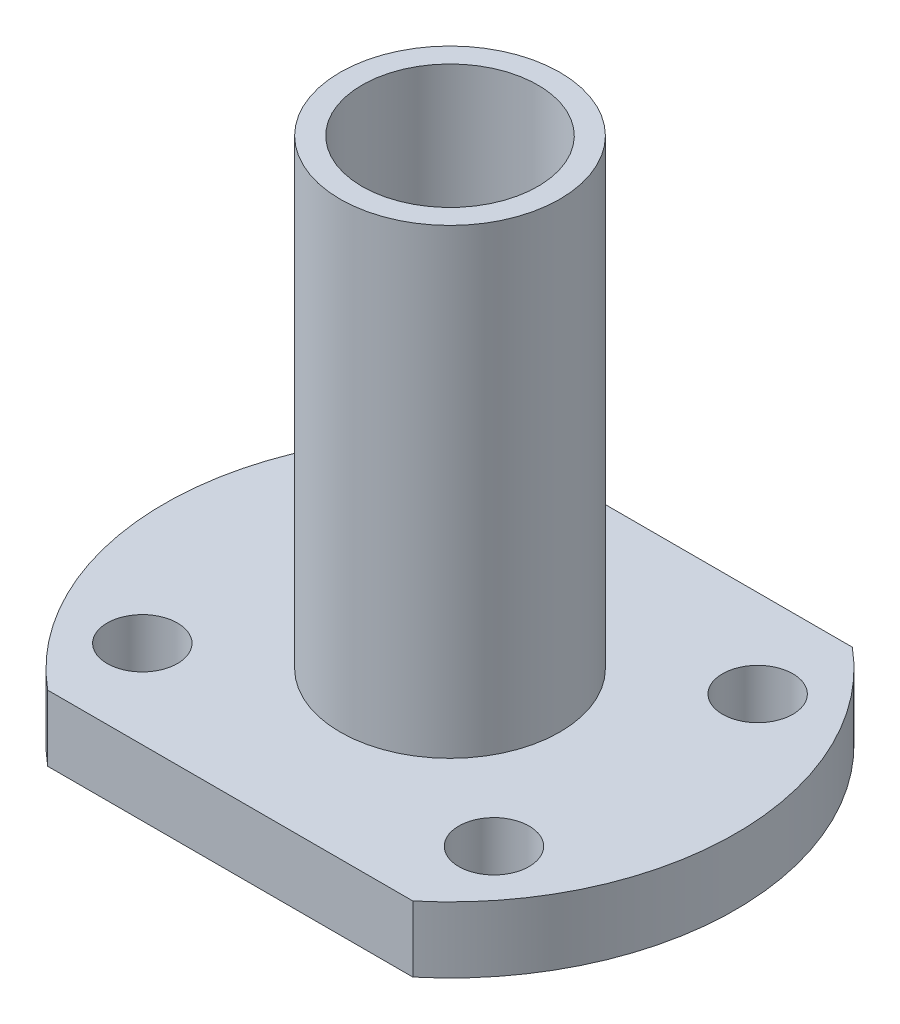
SolidWorks part; units mm, degrees
material "AISI 304"
ref_plane "Front Plane" through (0, 0, 0) normal (0, 0, 1) x (1, 0, 0)
ref_plane "Top Plane" through (0, 0, 0) normal (0, 1, 0) x (1, 0, 0)
ref_plane "Right Plane" through (0, 0, 0) normal (1, 0, 0) x (0, 0, -1)
sketch "Sketch1" plane through (0, 0, 0) normal (0, 1, 0) x (1, 0, 0)
  circle A0 centre (0, 0) radius 5
  dimension "D1" = 10
extrude "Boss-Extrude1" add sketch "Sketch1" along normal blind 24 contours A0
ref_plane "Plane1" through (0, 0, 0) normal (0, 1, 0) x (1, 0, 0)
sketch "Sketch2" plane through (0, 0, 0) normal (0, 1, 0) x (1, 0, 0)
  line L1 (-13, 10) -> (13, 10)
  line L2 (-13, 10) -> (-13, -10)
  line L3 (-13, -10) -> (13, -10)
  line L4 (13, 10) -> (13, -10)
  line L5 (-13, 10) -> (13, -10) construction
  line L6 (-13, -10) -> (13, 10) construction
  circle A0 centre (0, 0) radius 13
  dimension "D1" = 26
  dimension "D2" = 20
extrude "Boss-Extrude2" add sketch "Sketch2" along normal blind 3 contours L3 A0 L1
sketch "Sketch3" plane through (0, 24, 0) normal (0, 1, 0) x (1, 0, 0)
  circle A0 centre (0, 0) radius 4
  dimension "D1" = 8
extrude "Cut-Extrude1" cut sketch "Sketch3" against normal through all
sketch "Sketch4" plane through (0, 3, 0) normal (0, 1, 0) x (1, 0, 0)
  line L1 (8, -6) -> (-8, -6)
  line L2 (8, -6) -> (8, 6)
  line L3 (8, 6) -> (-8, 6)
  line L4 (-8, -6) -> (-8, 6)
  line L5 (8, -6) -> (-8, 6) construction
  line L6 (8, 6) -> (-8, -6) construction
  point P0 (0, 0)
  dimension "D1" = 12
  dimension "D2" = 16
hole_wizard "Ø3.2 (3.2) Diameter Hole1" positions "3DSketch1" profile "Sketch5" hole size "Ø3.2" standard "ISO" end condition through all
sketch3d "3DSketch1"
  point P0 (8, 3, 6)
  point P3 (8, 3, -6)
  point P6 (-8, 3, -6)
  point P9 (-8, 3, 6)
sketch "Sketch5" plane through (8, 3, 6) normal (1, 0, 0) x (0, 0, 1)
  line L0 (0, 0) -> (0, 3)
  line L1 (0, 3) -> (1.6, 3)
  line L2 (1.6, 3) -> (1.6, 0)
  line L5 (1.6, 0) -> (0, 0)
  line L11 (0, -6.35) -> (0, 107.95) construction
  dimension "Thru Hole Dia." = 3.2
  dimension "Thru Hole Depth" = 3
